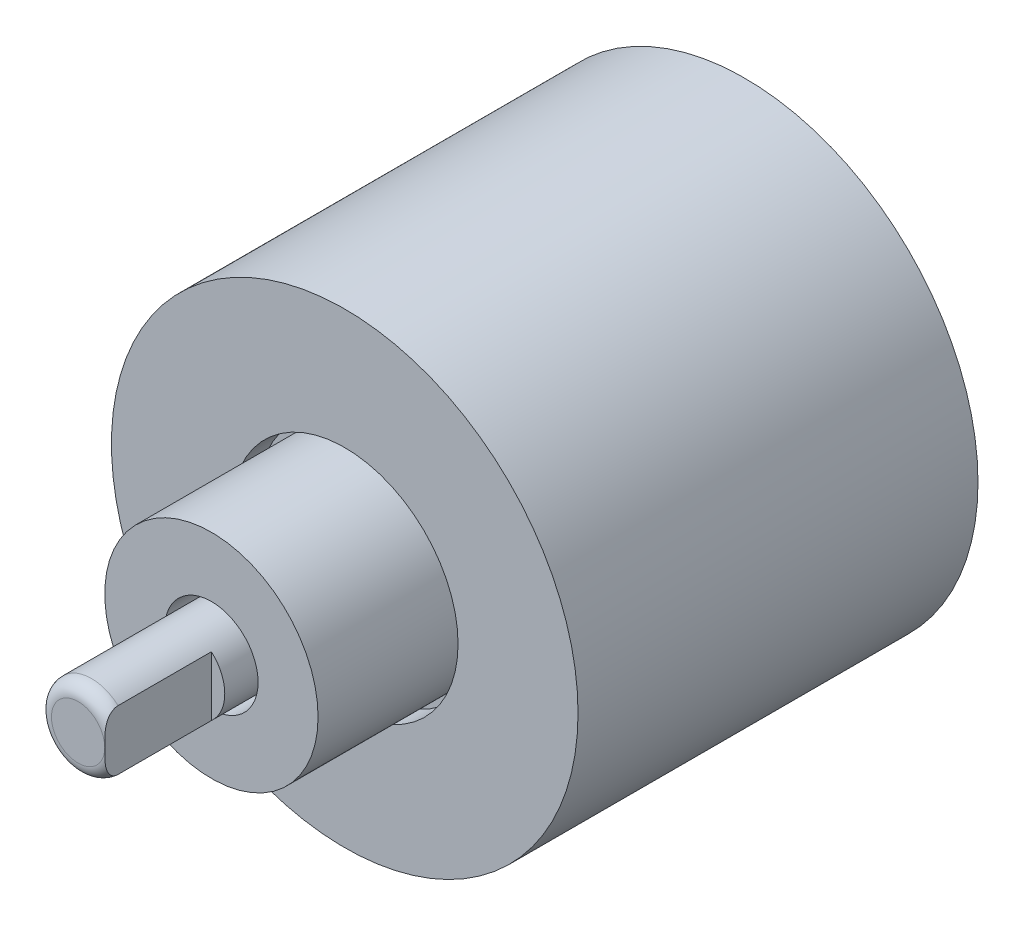
SolidWorks part; units mm, degrees
ref_plane "前视" through (0, 0, 0) normal (0, 0, 1) x (1, 0, 0)
ref_plane "上视" through (0, 0, 0) normal (0, 1, 0) x (1, 0, 0)
ref_plane "右视" through (0, 0, 0) normal (1, 0, 0) x (0, 0, -1)
sketch "草图1" plane through (0, 0, 0) normal (0, 0, 1) x (1, 0, 0)
  circle A0 centre (0, 0) radius 17.5
  dimension "D1" = 35
extrude "凸台-拉伸1" add sketch "草图1" along normal blind 30
sketch "草图2" plane through (0, 0, 30) normal (0, 0, 1) x (1, 0, 0)
  circle A0 centre (0, 0) radius 8
  dimension "D1" = 16
extrude "凸台-拉伸2" add sketch "草图2" along normal blind 10
sketch "草图3" plane through (0, 0, 30) normal (0, 0, 1) x (1, 0, 0)
  circle A0 centre (0, 0) radius 8.5
  circle A1 centre (0, 0) radius 8
  circle A2 centre (0, 0) radius 8 construction
  dimension "D1" = 0.5
extrude "切除-拉伸1" cut sketch "草图3" against normal blind 2
sketch "草图4" plane through (0, 0, 40) normal (0, 0, 1) x (1, 0, 0)
  circle A0 centre (0, 0) radius 3
  dimension "D1" = 6
extrude "凸台-拉伸3" add sketch "草图4" along normal blind 10
sketch "草图5" plane through (0, 0, 40) normal (0, 0, 1) x (1, 0, 0)
  circle A0 centre (0, 0) radius 3
  circle A1 centre (0, 0) radius 3.5
  circle A2 centre (0, 0) radius 3 construction
  dimension "D1" = 0.5
extrude "切除-拉伸2" cut sketch "草图5" against normal blind 12
fillet "圆角1" radius 1 1 edges at (3, 0, 50)
sketch "草图6" plane through (0, 0, 50) normal (0, 0, 1) x (1, 0, 0)
  line L1 (2, 3.6774) -> (4.5553, 3.6774)
  line L2 (2, 3.6774) -> (2, -5.6856)
  line L3 (2, -5.6856) -> (4.5553, -5.6856)
  line L4 (4.5553, 3.6774) -> (4.5553, -5.6856)
  circle A0 centre (0, 0) radius 3 construction
  dimension "D1" = 2
extrude "切除-拉伸3" cut sketch "草图6" against normal blind 8
